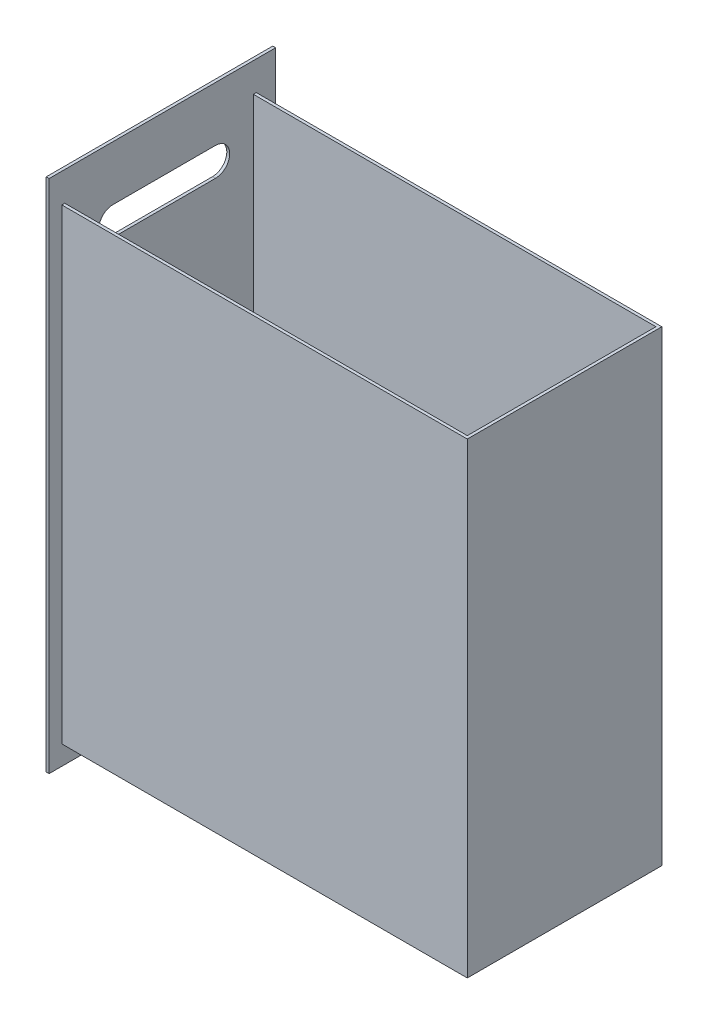
SolidWorks part; units mm, degrees
ref_plane "前视基准面" through (0, 0, 0) normal (0, 0, 1) x (1, 0, 0)
ref_plane "上视基准面" through (0, 0, 0) normal (0, 1, 0) x (1, 0, 0)
ref_plane "右视基准面" through (0, 0, 0) normal (1, 0, 0) x (0, 0, -1)
sketch "草图1" plane through (0, 0, 0) normal (0, 1, 0) x (1, 0, 0)
  line L1 (-210, -100) -> (210, -100)
  line L2 (-210, -100) -> (-210, 100)
  line L3 (-210, 100) -> (210, 100)
  line L4 (210, -100) -> (210, 100)
  line L5 (-210, -100) -> (210, 100) construction
  line L6 (-210, 100) -> (210, -100) construction
  point P0 (0, 0)
  dimension "D1" = 420
  dimension "D2" = 200
extrude "凸台-拉伸1" add sketch "草图1" along normal blind 3
sketch "草图2" plane through (0, 3, 0) normal (0, 1, 0) x (1, 0, 0)
  line L1 (-210, -100) -> (210, -100)
  line L2 (-210, -100) -> (-210, 100)
  line L3 (-210, 100) -> (210, 100)
  line L4 (210, -100) -> (210, 100)
  line L5 (-210, -100) -> (210, 100) construction
  line L6 (-210, 100) -> (210, -100) construction
  point P0 (0, 0)
extrude "拉伸-薄壁1" add sketch "草图2" along normal blind 477 thin thin type one direction reverse wall 3
sketch "草图4" plane through (-210, 0, 0) normal (-1, 0, 0) x (0, 0, 1)
  line L0 (-100, 480) -> (-100, 0) construction
  line L1 (-120, 510) -> (113, 510)
  line L2 (-120, 510) -> (-120, -20)
  line L3 (-120, -20) -> (113, -20)
  line L4 (113, 510) -> (113, -20)
  line L5 (100, 480) -> (100, 0) construction
  line L6 (-100, 0) -> (100, 0) construction
  dimension "D1" = 20
  dimension "D2" = 13
  dimension "D3" = 20
  dimension "D4" = 530
extrude "凸台-拉伸2" add sketch "草图4" against normal blind 3
sketch "草图5" plane through (-210, 0, 0) normal (-1, 0, 0) x (0, 0, 1)
  line L0 (-58.0546, 439.2895) -> (47.3228, 439.2895) construction
  line L1 (-58.0546, 453.9252) -> (47.3228, 453.9252)
  line L2 (-58.0546, 424.6537) -> (47.3228, 424.6537)
  arc A0 (-58.0546, 453.9252) -> (-58.0546, 424.6537) centre (-58.0546, 439.2895) ccw
  arc A1 (47.3228, 424.6537) -> (47.3228, 453.9252) centre (47.3228, 439.2895) ccw
  point P2 (-5.3659, 439.2895)
extrude "切除-拉伸1" cut sketch "草图5" against normal blind 3
